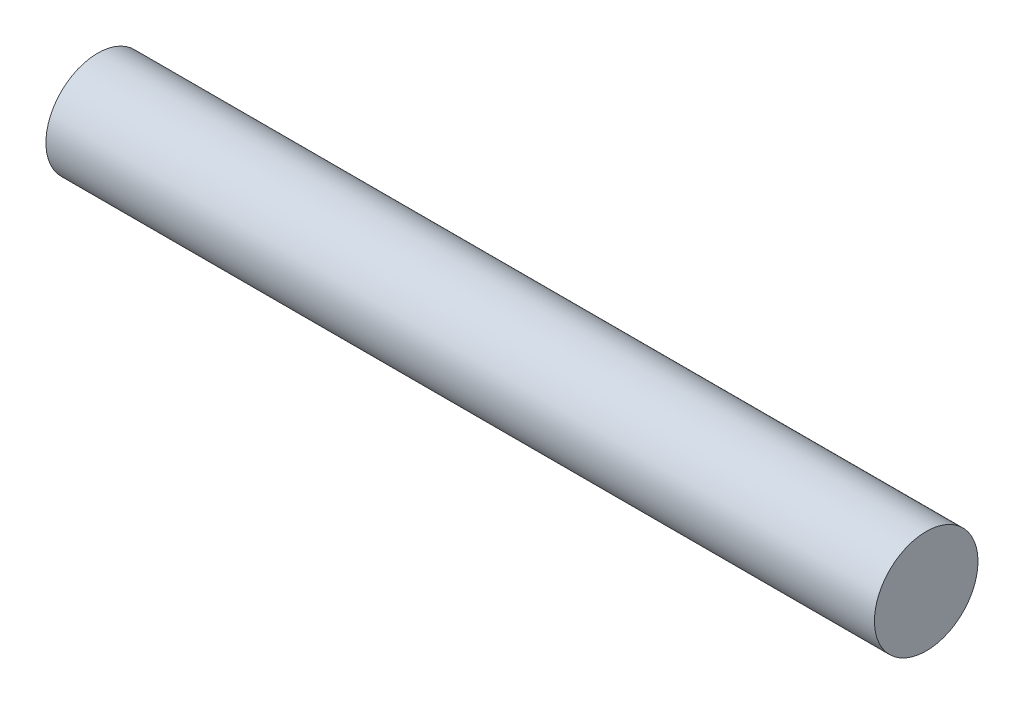
SolidWorks part; units mm, degrees
ref_plane "Front Plane" through (0, 0, 0) normal (0, 0, 1) x (1, 0, 0)
ref_plane "Top Plane" through (0, 0, 0) normal (0, 1, 0) x (1, 0, 0)
ref_plane "Right Plane" through (0, 0, 0) normal (1, 0, 0) x (0, 0, -1)
sketch "Sketch1" plane through (0, 0, 0) normal (1, 0, 0) x (0, 0, -1)
  circle A0 centre (0, 0) radius 0.7937
  dimension "D1" = 1.5875
extrude "Boss-Extrude1" add sketch "Sketch1" along normal mid plane 12.7
